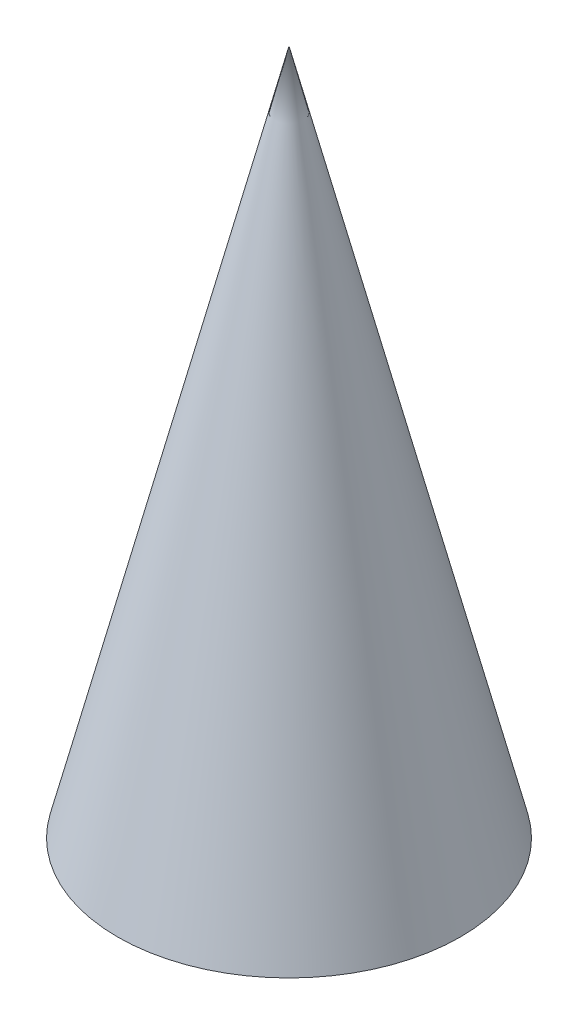
SolidWorks part; units mm, degrees
ref_plane "Alzado" through (0, 0, 0) normal (0, 0, 1) x (1, 0, 0)
ref_plane "Planta" through (0, 0, 0) normal (0, 1, 0) x (1, 0, 0)
ref_plane "Vista lateral" through (0, 0, 0) normal (1, 0, 0) x (0, 0, -1)
sketch "Croquis1" plane through (0, 0, 0) normal (0, 0, 1) x (1, 0, 0)
  line L0 (0, 0) -> (25, 0)
  line L1 (55, 0) -> (-55, 0) construction
  line L2 (25, 0) -> (0, 100)
  line L3 (0, -55) -> (0, 55) construction
  line L4 (0, 100) -> (0, 0)
  dimension "D1" = 25
  dimension "D2" = 100
revolve "Revolución1" add sketch "Croquis1" angle 360 about L4
